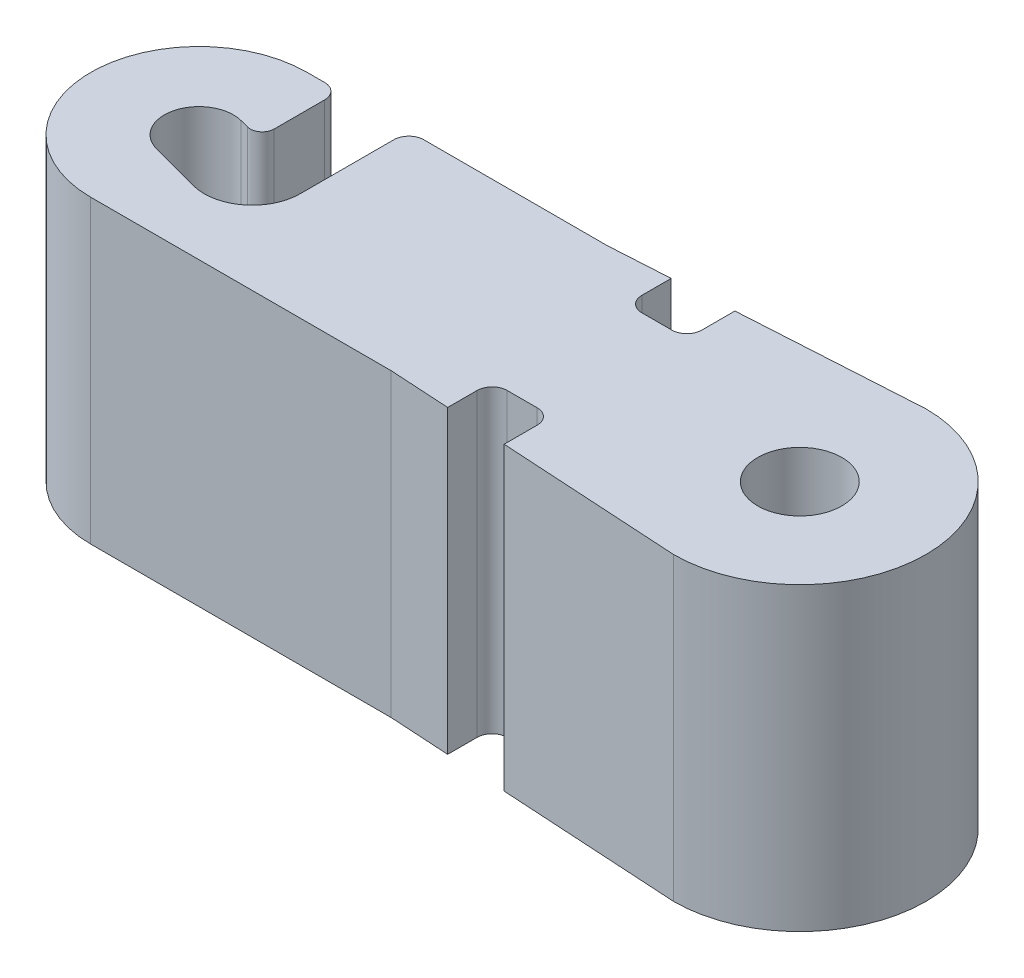
SolidWorks part; units mm, degrees
ref_plane "Front Plane" through (0, 0, 0) normal (0, 0, 1) x (1, 0, 0)
ref_plane "Top Plane" through (0, 0, 0) normal (0, 1, 0) x (1, 0, 0)
ref_plane "Right Plane" through (0, 0, 0) normal (1, 0, 0) x (0, 0, -1)
sketch "Sketch3" plane through (0, 0, 0) normal (0, 1, 0) x (1, 0, 0)
  line L0 (-5, 0.75) -> (0, 1.05) construction
  line L3 (0, -1.05) -> (-5, -0.75) construction
  line L4 (-2.5, 0.9) -> (-2, 0.93)
  line L6 (-4.25, 0) -> (-5.75, 0) construction
  line L7 (-2, 0.93) -> (-2, 0.56)
  line L8 (-2.5, 0.9) -> (-5, 0.9)
  line L9 (-2.5, 0.9) -> (-2.5, -0.9) construction
  line L10 (-2.5, -0.9) -> (-5, -0.9)
  line L11 (-5, 0.9) -> (-5, -0.9) construction
  line L12 (-2, 0.96) -> (-1.5, 0.96) construction
  line L13 (-2, 0.96) -> (-2, 0.56) construction
  line L14 (-2, 0.56) -> (-1.5, 0.56)
  line L15 (-1.5, 0.96) -> (-1.5, 0.56)
  line L16 (-1.5, -0.56) -> (-2, -0.56)
  line L17 (-1.5, -0.56) -> (-1.5, -0.96)
  line L18 (-1.5, -0.96) -> (-2, -0.96) construction
  line L19 (-2, -0.56) -> (-2, -0.96) construction
  line L21 (-2.5, -0.9) -> (-2, -0.93)
  line L22 (-2, -0.93) -> (-2, -0.56)
  line L23 (-1.5, 0.96) -> (0, 1.05)
  line L24 (0, -1.05) -> (-1.5, -0.96)
  circle A2 centre (0, 0) radius 0.6 construction
  circle A3 centre (0, 0) radius 0.4 construction
  circle A4 centre (-5, 0) radius 0.35 construction
  circle A5 centre (0, 0) radius 1.05 construction
  circle A6 centre (-5, 0) radius 0.75 construction
  arc A7 (-5, 0.9) -> (-5, -0.9) centre (-5, 0) ccw
  arc A8 (0, 1.05) -> (0, -1.05) centre (0, 0) cw
  point P4 (-2, -0.93)
  point P15 (-5, 0)
  point P16 (-2, 0.93)
  point P22 (-5, 0)
  dimension "D2" = 1.2
  dimension "D3" = 0.8
  dimension "D4" = 0.7
  dimension "D6" = 5
  dimension "D1" = 1.5
  dimension "D5" = 2.1
  dimension "D7" = 0.4
  dimension "D9" = 2.5
  dimension "D10" = 1.8
  dimension "D11" = 2.5
  dimension "D12" = 0.5
  dimension "D14" = 1.5
extrude "Boss-Extrude1" add sketch "Sketch3" along normal blind 2.5 contours L8 A7 L10 L21 L22 L16 L17 L24 A8 L23 L15 L14 L7 L4
sketch "Sketch4" plane through (0, 2.5, 0) normal (0, 1, 0) x (1, 0, 0)
  line L4 (-4.9256, 0.2777) -> (-4.7284, 0.2249)
  line L5 (-4.7284, 0.2249) -> (-4.7284, 0.9) construction
  line L7 (-2.5, 0.9) -> (-5, 0.9) construction
  line L8 (-4.7284, 0.9) -> (-4.1534, 0.9)
  line L9 (-4.1534, 0.9) -> (-4.1534, -0.5245)
  line L10 (-4.7284, 0.9) -> (-4.7284, 0.2249)
  line L11 (-5.0744, -0.2777) -> (-4.1534, -0.5245)
  line L12 (-4.9256, 0.2777) -> (-5.0744, -0.2777) construction
  line L13 (-5.6391, 0) -> (-3.7248, 0) construction
  circle A0 centre (0, 0) radius 0.35
  circle A1 centre (-5, 0) radius 0.375 construction
  circle A3 centre (-5, 0) radius 0.2875 construction
  arc A7 (-4.9256, 0.2777) -> (-5.0744, -0.2777) centre (-5, 0) ccw
  point P9 (0, 0)
  point P11 (0, 0)
  dimension "D1" = 0.7
  dimension "D2" = 0.75
  dimension "D4" = 0.575
  dimension "D3" = 0.575
  dimension "D5" = 0.575
  dimension "D6" = 75
extrude "Through Holes" cut sketch "Sketch4" against normal through all
fillet "Fillet1" radius 0.125 6 edges at (-2, 1.25, 0.56) (-1.5, 1.25, 0.56) (-1.5, 1.25, -0.56) (-2, 1.25, -0.56) (-4.7284, 1.25, -0.9) (-4.1534, 1.25, -0.9)
fillet "Fillet2" radius 0.4 1 edges at (-4.1534, 1.25, 0.5245)
fillet "Fillet3" radius 0.1 1 edges at (-4.7284, 1.25, -0.2249)
